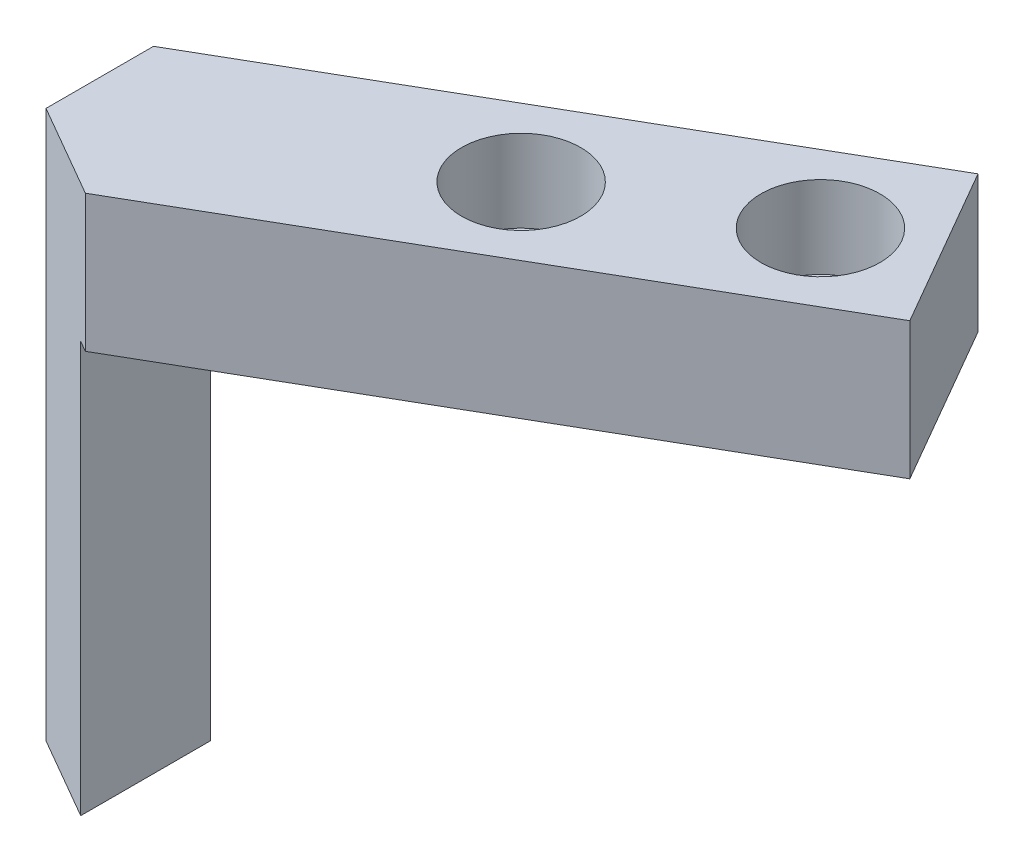
SolidWorks part; units mm, degrees
ref_plane "前基準面" through (0, 0, 0) normal (0, 0, 1) x (1, 0, 0)
ref_plane "上基準面" through (0, 0, 0) normal (0, 1, 0) x (1, 0, 0)
ref_plane "右基準面" through (0, 0, 0) normal (1, 0, 0) x (0, 0, -1)
ref_plane "平面1" through (0, -5, 0) normal (0, -1, 0) x (1, 0, 0)
sketch "草圖1" plane through (0, -5, 0) normal (0, -1, 0) x (1, 0, 0)
  line L0 (3.4, 1.963) -> (0, 0)
  line L1 (0, 0) -> (0, -3.926)
  line L2 (0, -3.926) -> (19.0846, -14.9445)
  line L3 (19.0846, -14.9445) -> (22.4846, -9.0555)
  line L4 (22.4846, -9.0555) -> (3.4, 1.963)
extrude "填料-伸長1" add sketch "草圖1" against normal blind 5
sketch "草圖2" plane through (0, -5, 0) normal (0, -1, 0) x (1, 0, 0)
  line L0 (3, 1.7321) -> (3, -2.9979)
  line L1 (3, -2.9979) -> (0, -2.9979)
  line L2 (0, -2.9979) -> (0, 0)
  line L3 (0, 0) -> (3, 1.7321)
extrude "填料-伸長2" add sketch "草圖2" along normal blind 15
hole_wizard "M2 六角頭機械螺釘的柱孔1" positions "草圖4" profile "草圖3" counterbore size "M2" standard "Ansi Metric"
sketch "草圖4" plane through (0, 0, 0) normal (0, 1, 0) x (1, 0, 0)
  point P0 (17.9267, 10.35)
  point P1 (10.9985, 6.35)
sketch "草圖3" plane through (17.9267, 0, -10.35) normal (1, 0, 0) x (0, 0, 1)
  line L0 (0, 0) -> (0, 20)
  line L1 (0, 20) -> (1.175, 20)
  line L3 (1.175, 20) -> (1.175, 3)
  line L4 (1.175, 3) -> (2.175, 3)
  line L5 (2.175, 3) -> (2.175, 0)
  line L7 (2.175, 0) -> (0, 0)
  line L11 (0, -6.35) -> (0, 107.95) construction
  dimension "貫穿孔直徑" = 2.35
  dimension "貫穿孔深度" = 20
  dimension "柱孔直徑" = 4.35
  dimension "柱孔深度" = 3
